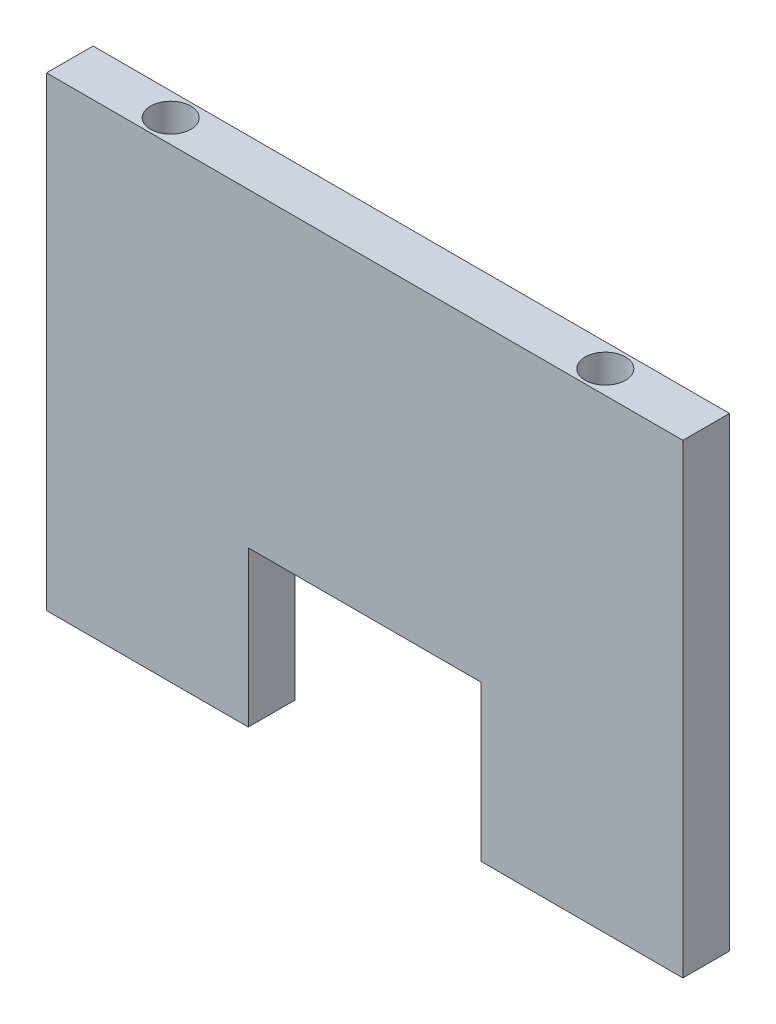
SolidWorks part; units mm, degrees
ref_plane "Front Plane" through (0, 0, 0) normal (0, 0, 1) x (1, 0, 0)
ref_plane "Top Plane" through (0, 0, 0) normal (0, 1, 0) x (1, 0, 0)
ref_plane "Right Plane" through (0, 0, 0) normal (1, 0, 0) x (0, 0, -1)
sketch "Sketch3" plane through (0, 0, 0) normal (0, 0, 1) x (1, 0, 0)
  line L1 (0, 0) -> (52.07, 0)
  line L2 (0, 0) -> (0, 38.1)
  line L3 (0, 38.1) -> (52.07, 38.1)
  line L4 (52.07, 0) -> (52.07, 38.1)
  dimension "D1" = 52.07
  dimension "D2" = 38.1
extrude "Boss-Extrude2" add sketch "Sketch3" along normal blind 3.81
sketch "Sketch4" plane through (0, 0, 3.81) normal (0, 0, 1) x (1, 0, 0)
  line L0 (26.035, 38.1) -> (26.035, -1.144) construction
  line L2 (0, 0) -> (52.07, 0) construction
  line L3 (16.51, 12.7) -> (35.56, 12.7)
  line L4 (16.51, 12.7) -> (16.51, 0)
  line L5 (16.51, 0) -> (35.56, 0)
  line L6 (35.56, 12.7) -> (35.56, 0)
  line L7 (16.51, 12.7) -> (35.56, 0) construction
  line L8 (16.51, 0) -> (35.56, 12.7) construction
  point P1 (26.035, 18.478)
  point P2 (26.035, 6.35)
  dimension "D1" = 26.035
  dimension "D2" = 19.05
  dimension "D3" = 12.7
extrude "Cut-Extrude1" cut sketch "Sketch4" against normal through all
ref_plane "Plane1" through (0, 19.05, 0) normal (0, 1, 0) x (1, 0, 0)
sketch "Sketch6" plane through (0, 0, 0) normal (0, -1, 0) x (1, 0, 0)
  line L0 (0, 3.81) -> (0, 0) construction
  line L1 (0, 3.81) -> (16.51, 3.81) construction
  line L2 (35.56, 0) -> (52.07, 0) construction
  line L3 (52.07, 3.81) -> (52.07, 0) construction
  circle A0 centre (8.255, 1.905) radius 1.651
  circle A1 centre (43.815, 1.905) radius 1.651
  point P5 (0, 1.905)
  point P8 (8.255, 3.81)
  point P12 (43.815, 0)
  point P15 (52.07, 1.905)
  dimension "D1" = 3.302
  dimension "D2" = 3.302
sketch "Sketch8" plane through (0, 38.1, 0) normal (0, 1, 0) x (1, 0, 0)
  circle A0 centre (8.255, -1.905) radius 1.651
  circle A1 centre (8.255, -1.905) radius 1.651 construction
  circle A2 centre (43.815, -1.905) radius 1.651
  circle A3 centre (43.815, -1.905) radius 1.651 construction
extrude "Cut-Extrude2" cut sketch "Sketch6" against normal blind 5.08
extrude "Cut-Extrude3" cut sketch "Sketch8" against normal blind 5.08
